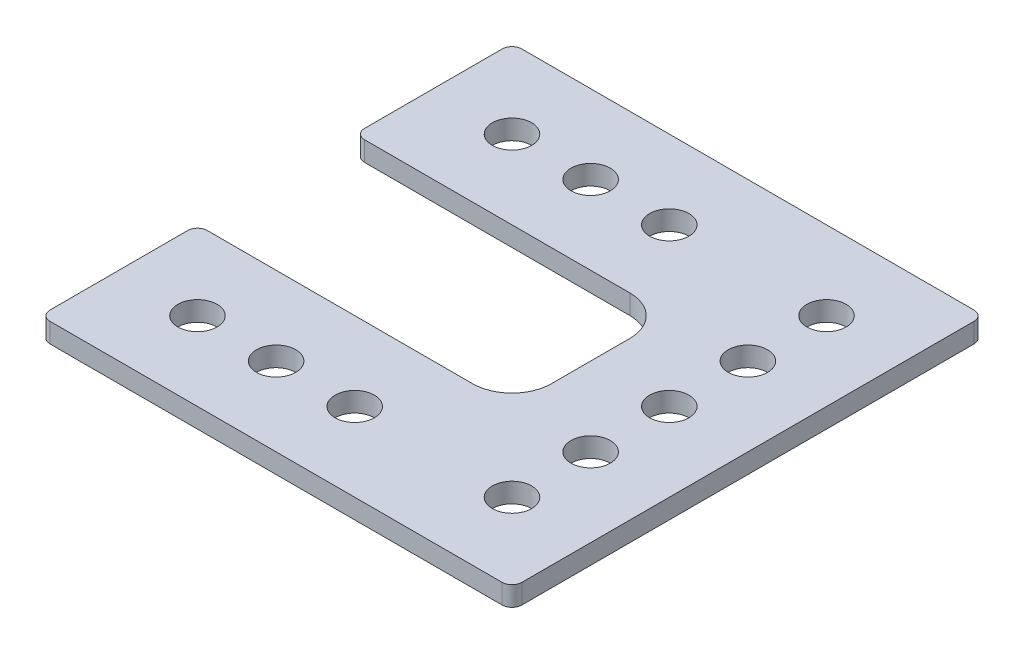
SolidWorks part; units mm, degrees
ref_plane "Front Plane" through (0, 0, 0) normal (0, 0, 1) x (1, 0, 0)
ref_plane "Top Plane" through (0, 0, 0) normal (0, 1, 0) x (1, 0, 0)
ref_plane "Right Plane" through (0, 0, 0) normal (1, 0, 0) x (0, 0, -1)
sketch "Sketch1" plane through (0, 0, 0) normal (0, 1, 0) x (1, 0, 0)
  line L0 (-63.5, 25.4) -> (-12.7, 25.4) construction
  line L1 (-12.7, -38.1) -> (12.7, -38.1)
  line L2 (-12.7, -12.7) -> (-12.7, 12.7)
  line L3 (-12.7, 38.1) -> (12.7, 38.1)
  line L4 (12.7, -38.1) -> (12.7, 38.1)
  line L5 (-12.7, -38.1) -> (12.7, 38.1) construction
  line L6 (-12.7, 38.1) -> (12.7, -38.1) construction
  line L7 (-63.5, 12.7) -> (-12.7, 12.7)
  line L8 (-63.5, 12.7) -> (-63.5, 38.1)
  line L9 (-63.5, 38.1) -> (-12.7, 38.1)
  line L10 (-63.5, -38.1) -> (-12.7, -38.1)
  line L11 (-63.5, 12.7) -> (-12.7, 38.1) construction
  line L12 (-63.5, 38.1) -> (-12.7, 12.7) construction
  line L13 (0, 38.1) -> (0, -38.1) construction
  line L14 (12.7, 0) -> (-12.7, 0) construction
  line L15 (-63.5, -12.7) -> (-12.7, -12.7)
  line L16 (-63.5, -12.7) -> (-63.5, -38.1)
  point P0 (0, 0)
  point P6 (-38.1, 25.4)
  point P19 (-38.1, -25.4)
  dimension "D1" = 25.4
  dimension "D2" = 76.2
  dimension "D3" = 50.8
  dimension "D4" = 25.4
extrude "Boss-Extrude1" add sketch "Sketch1" along normal blind 3.175
sketch "Sketch2" plane through (0, 3.175, 0) normal (0, 1, 0) x (1, 0, 0)
  line L0 (0, 0) -> (0, 38.1) construction
  line L1 (12.7, 38.1) -> (-63.5, 38.1) construction
  line L2 (0, 0) -> (0, -38.1) construction
  line L3 (-63.5, -38.1) -> (12.7, -38.1) construction
  line L4 (-63.5, -25.4) -> (12.7, -25.4) construction
  line L5 (-63.5, -12.7) -> (-63.5, -38.1) construction
  line L6 (12.7, -38.1) -> (12.7, 38.1) construction
  line L7 (-63.5, 25.4) -> (12.7, 25.4) construction
  line L8 (-63.5, 38.1) -> (-63.5, 12.7) construction
  line L9 (-12.7, 0) -> (12.7, 0) construction
  line L10 (-12.7, 12.7) -> (-12.7, -12.7) construction
  circle A0 centre (0, 0) radius 3.175
  circle A1 centre (0, 12.7) radius 3.175
  circle A2 centre (0, 25.4) radius 3.175
  circle A3 centre (0, -25.4) radius 3.175
  circle A4 centre (0, -12.7) radius 3.175
  circle A5 centre (-50.8, 25.4) radius 3.175
  circle A6 centre (-38.1, 25.4) radius 3.175
  circle A7 centre (-25.4, 25.4) radius 3.175
  circle A8 centre (-25.4, -25.4) radius 3.175
  circle A9 centre (-38.1, -25.4) radius 3.175
  circle A10 centre (-50.8, -25.4) radius 3.175
  dimension "D1" = 3
  dimension "D2" = 6.35
  dimension "D3" = 6.35
  dimension "D4" = 12.7
  dimension "D5" = 3
extrude "Cut-Extrude1" cut sketch "Sketch2" against normal through all
fillet "Fillet1" radius 1.5875 6 edges at (12.7, 1.5875, 38.1) (12.7, 1.5875, -38.1) (-63.5, 1.5875, -38.1) (-63.5, 1.5875, 38.1) (-63.5, 1.5875, 12.7) (-63.5, 1.5875, -12.7)
fillet "Fillet2" radius 6.35 2 edges at (-12.7, 1.5875, 12.7) (-12.7, 1.5875, -12.7)
